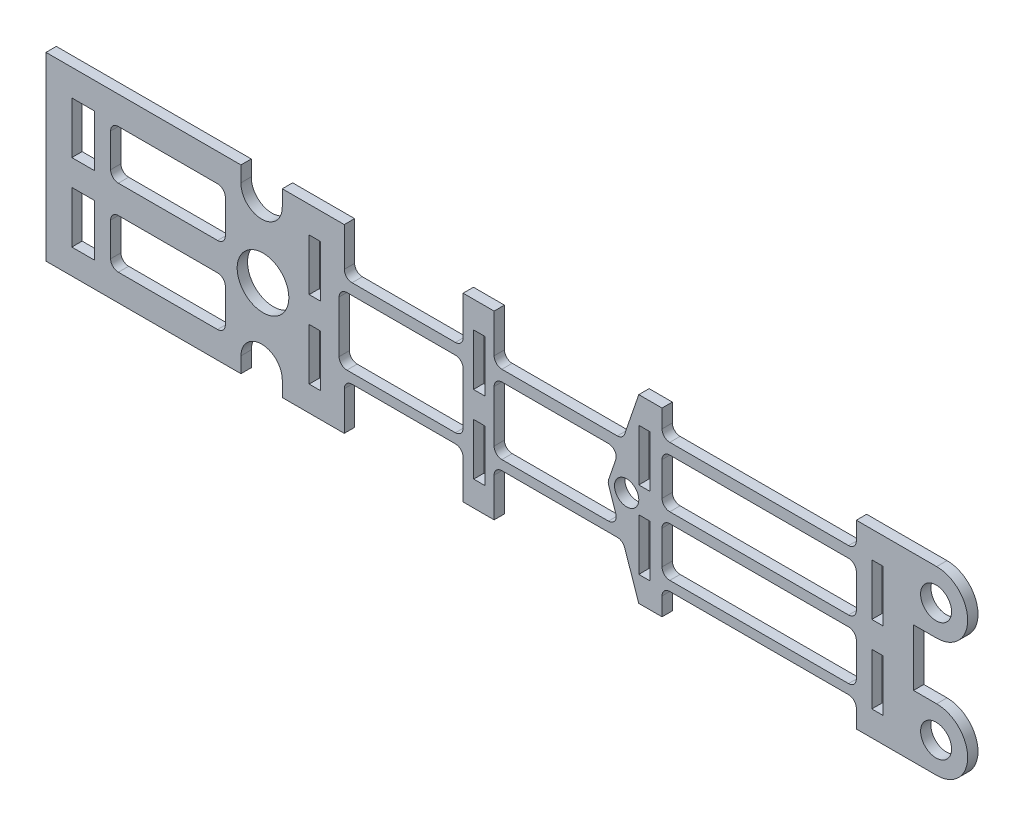
SolidWorks part; units mm, degrees
ref_plane "前视基准面" through (0, 0, 0) normal (0, 0, 1) x (1, 0, 0)
ref_plane "上视基准面" through (0, 0, 0) normal (0, 1, 0) x (1, 0, 0)
ref_plane "右视基准面" through (0, 0, 0) normal (1, 0, 0) x (0, 0, -1)
sketch "Model" plane through (0, 0, 0) normal (0, 0, 1) x (1, 0, 0)
  line L0 (55.9533, 32.4051) -> (58.1533, 32.4051)
  line L1 (58.1533, 32.4051) -> (58.1533, 22.4051)
  line L2 (58.1533, 22.4051) -> (55.9533, 22.4051)
  line L3 (55.9533, 22.4051) -> (55.9533, 32.4051)
  line L4 (55.9533, 7.4051) -> (58.1533, 7.4051)
  line L5 (58.1533, 7.4051) -> (58.1533, 17.4051)
  line L6 (58.1533, 17.4051) -> (55.9533, 17.4051)
  line L7 (55.9533, 17.4051) -> (55.9533, 7.4051)
  line L8 (167.0525, 22.4051) -> (164.8525, 22.4051)
  line L9 (164.8525, 22.4051) -> (164.8525, 32.4051)
  line L10 (164.8525, 32.4051) -> (167.0525, 32.4051)
  line L11 (167.0525, 32.4051) -> (167.0525, 22.4051)
  line L12 (167.0525, 7.4051) -> (167.0525, 17.4051)
  line L13 (167.0525, 17.4051) -> (164.8525, 17.4051)
  line L14 (164.8525, 17.4051) -> (164.8525, 7.4051)
  line L15 (164.8525, 7.4051) -> (167.0525, 7.4051)
  line L16 (119.7532, 32.4051) -> (121.9532, 32.4051)
  line L17 (121.9532, 32.4051) -> (121.9532, 22.4051)
  line L18 (121.9532, 22.4051) -> (119.7532, 22.4051)
  line L19 (119.7532, 22.4051) -> (119.7532, 32.4051)
  line L20 (119.7532, 7.4051) -> (121.9532, 7.4051)
  line L21 (121.9532, 7.4051) -> (121.9532, 17.4051)
  line L22 (121.9532, 17.4051) -> (119.7532, 17.4051)
  line L23 (119.7532, 17.4051) -> (119.7532, 7.4051)
  line L24 (87.7533, 32.4051) -> (89.9533, 32.4051)
  line L25 (89.9533, 32.4051) -> (89.9533, 22.4075)
  line L26 (89.9533, 22.4075) -> (87.7533, 22.4051)
  line L27 (87.7533, 22.4051) -> (87.7533, 32.4051)
  line L28 (87.7999, 7.3998) -> (89.9999, 7.3998)
  line L29 (89.9999, 7.3998) -> (89.9533, 17.3998)
  line L30 (89.9533, 17.3998) -> (87.7999, 17.3998)
  line L31 (87.7999, 17.3998) -> (87.7999, 7.3998)
  line L32 (63.2533, 26.4051) -> (84.2533, 26.4051)
  line L33 (85.7533, 24.9051) -> (85.7533, 14.9051)
  line L34 (84.2533, 13.4051) -> (63.2533, 13.4051)
  line L35 (61.7533, 14.9051) -> (61.7533, 24.9051)
  line L36 (113.8817, 13.4051) -> (93.2533, 13.4051)
  line L37 (91.7533, 14.9051) -> (91.7533, 24.9051)
  line L38 (93.2533, 26.4051) -> (113.8817, 26.4051)
  line L39 (115.3007, 24.4186) -> (113.92, 20.3916)
  line L40 (113.92, 19.4186) -> (115.3007, 15.3916)
  line L41 (42.7544, 5.5422) -> (42.7544, 2.5422)
  line L42 (62.7533, 37.5422) -> (62.7533, 30.0422)
  line L43 (64.2533, 28.5422) -> (84.2533, 28.5422)
  line L44 (85.7533, 30.0422) -> (85.7533, 37.5422)
  line L45 (85.7533, 37.5422) -> (91.7533, 37.5422)
  line L46 (91.7533, 37.5422) -> (91.7533, 30.0422)
  line L47 (93.2533, 28.5422) -> (115.596, 28.5422)
  line L48 (117.015, 29.5557) -> (119.7532, 37.5422)
  line L49 (119.7532, 37.5422) -> (124.2525, 37.5422)
  line L50 (124.2525, 37.5422) -> (124.2525, 34.0422)
  line L51 (125.7525, 32.5422) -> (160.3525, 32.5422)
  line L52 (161.8525, 34.0422) -> (161.8525, 37.5422)
  line L53 (161.8525, 37.5422) -> (177.4044, 37.5422)
  line L54 (177.4044, 25.5422) -> (172.9225, 25.5422)
  line L55 (172.9225, 25.5422) -> (172.9225, 14.5422)
  line L56 (172.9225, 14.5422) -> (177.4044, 14.5422)
  line L57 (177.4044, 2.5422) -> (161.8525, 2.5422)
  line L58 (161.8525, 2.5422) -> (161.8525, 6.0422)
  line L59 (160.3525, 7.5422) -> (125.7525, 7.5422)
  line L60 (124.2525, 6.0422) -> (124.2525, 2.5422)
  line L61 (124.2525, 2.5422) -> (119.7532, 2.5422)
  line L62 (119.7532, 2.5422) -> (117.015, 10.5287)
  line L63 (115.596, 11.5422) -> (93.2533, 11.5422)
  line L64 (91.7533, 10.0422) -> (91.7533, 2.5422)
  line L65 (91.7533, 2.5422) -> (85.7533, 2.5422)
  line L66 (85.7533, 2.5422) -> (85.7533, 10.0422)
  line L67 (84.2533, 11.5422) -> (64.2533, 11.5422)
  line L68 (62.7533, 10.0422) -> (62.7533, 2.5422)
  line L69 (62.7533, 2.5422) -> (50.7523, 2.5422)
  line L70 (50.7523, 2.5422) -> (50.7538, 5.475)
  line L71 (42.7544, 2.5422) -> (5.0248, 2.5422)
  line L72 (42.7544, 34.5422) -> (42.7544, 37.5422)
  line L73 (62.7533, 37.5422) -> (50.7523, 37.5422)
  line L74 (50.7523, 37.5422) -> (50.7523, 34.5422)
  line L75 (42.7544, 37.5422) -> (5.0248, 37.5422)
  line L76 (5.0248, 2.5422) -> (5.0248, 37.5422)
  line L77 (161.8525, 22.4051) -> (161.8525, 28.9051)
  line L78 (160.3525, 30.4051) -> (125.7525, 30.4051)
  line L79 (124.2525, 28.9051) -> (124.2525, 22.4051)
  line L80 (125.7525, 20.9051) -> (160.3525, 20.9051)
  line L81 (124.2525, 17.4051) -> (124.2525, 10.9051)
  line L82 (125.7525, 9.4051) -> (160.3525, 9.4051)
  line L83 (161.8525, 10.9051) -> (161.8525, 17.4051)
  line L84 (160.3525, 18.9051) -> (125.7525, 18.9051)
  line L85 (10.0248, 32.4051) -> (14.4248, 32.4051)
  line L86 (10.0248, 22.4051) -> (14.4248, 22.4051)
  line L87 (10.0248, 17.4051) -> (14.4248, 17.4051)
  line L88 (10.0248, 7.4051) -> (14.4248, 7.4051)
  line L89 (10.0248, 32.4051) -> (10.0248, 22.4051)
  line L90 (14.4248, 32.4051) -> (14.4248, 22.4051)
  line L91 (10.0248, 17.4051) -> (10.0248, 7.4051)
  line L92 (14.4248, 17.4051) -> (14.4248, 7.4051)
  line L93 (19.0245, 17.1915) -> (38.2285, 17.1915)
  line L94 (39.7285, 15.6915) -> (39.7285, 9.1915)
  line L95 (38.2285, 7.6915) -> (19.0245, 7.6915)
  line L96 (17.5245, 9.1915) -> (17.5245, 15.6915)
  line L97 (19.0245, 22.6187) -> (38.2285, 22.6187)
  line L98 (39.7285, 24.1187) -> (39.7285, 30.6187)
  line L99 (38.2285, 32.1187) -> (19.0245, 32.1187)
  line L100 (17.5245, 30.6187) -> (17.5245, 24.1187)
  circle A0 centre (177.2919, 31.4051) radius 3
  circle A1 centre (177.2919, 8.4051) radius 3
  circle A2 centre (117.4032, 19.9051) radius 2.35
  circle A3 centre (47.0264, 19.9051) radius 5
  arc A4 (63.2533, 26.4051) -> (61.7533, 24.9051) centre (63.2533, 24.9051) ccw
  arc A5 (85.7533, 24.9051) -> (84.2533, 26.4051) centre (84.2533, 24.9051) ccw
  arc A6 (84.2533, 13.4051) -> (85.7533, 14.9051) centre (84.2533, 14.9051) ccw
  arc A7 (61.7533, 14.9051) -> (63.2533, 13.4051) centre (63.2533, 14.9051) ccw
  arc A8 (50.7538, 5.475) -> (42.7544, 5.5422) centre (46.7541, 5.5086) ccw
  arc A9 (62.7533, 30.0422) -> (64.2533, 28.5422) centre (64.2533, 30.0422) ccw
  arc A10 (84.2533, 28.5422) -> (85.7533, 30.0422) centre (84.2533, 30.0422) ccw
  arc A11 (91.7533, 30.0422) -> (93.2533, 28.5422) centre (93.2533, 30.0422) ccw
  arc A12 (115.596, 28.5422) -> (117.015, 29.5557) centre (115.596, 30.0422) ccw
  arc A13 (124.2525, 34.0422) -> (125.7525, 32.5422) centre (125.7525, 34.0422) ccw
  arc A14 (160.3525, 32.5422) -> (161.8525, 34.0422) centre (160.3525, 34.0422) ccw
  arc A15 (177.4044, 25.5422) -> (177.4044, 37.5422) centre (177.4044, 31.5422) ccw
  arc A16 (177.4044, 2.5422) -> (177.4044, 14.5422) centre (177.4044, 8.5422) ccw
  arc A17 (161.8525, 6.0422) -> (160.3525, 7.5422) centre (160.3525, 6.0422) ccw
  arc A18 (125.7525, 7.5422) -> (124.2525, 6.0422) centre (125.7525, 6.0422) ccw
  arc A19 (117.015, 10.5287) -> (115.596, 11.5422) centre (115.596, 10.0422) ccw
  arc A20 (93.2533, 11.5422) -> (91.7533, 10.0422) centre (93.2533, 10.0422) ccw
  arc A21 (85.7533, 10.0422) -> (84.2533, 11.5422) centre (84.2533, 10.0422) ccw
  arc A22 (64.2533, 11.5422) -> (62.7533, 10.0422) centre (64.2533, 10.0422) ccw
  arc A23 (42.7544, 34.5422) -> (50.7523, 34.5422) centre (46.7533, 34.4579) ccw
  arc A24 (19.0245, 17.1915) -> (17.5245, 15.6915) centre (19.0245, 15.6915) ccw
  arc A25 (39.7285, 15.6915) -> (38.2285, 17.1915) centre (38.2285, 15.6915) ccw
  arc A26 (38.2285, 7.6915) -> (39.7285, 9.1915) centre (38.2285, 9.1915) ccw
  arc A27 (17.5245, 9.1915) -> (19.0245, 7.6915) centre (19.0245, 9.1915) ccw
  arc A28 (17.5245, 24.1187) -> (19.0245, 22.6187) centre (19.0245, 24.1187) ccw
  arc A29 (38.2285, 22.6187) -> (39.7285, 24.1187) centre (38.2285, 24.1187) ccw
  arc A30 (39.7285, 30.6187) -> (38.2285, 32.1187) centre (38.2285, 30.6187) ccw
  arc A31 (19.0245, 32.1187) -> (17.5245, 30.6187) centre (19.0245, 30.6187) ccw
  arc A32 (113.8817, 13.4051) -> (115.3007, 15.3916) centre (113.8817, 14.9051) ccw
  arc A33 (91.7533, 14.9051) -> (93.2533, 13.4051) centre (93.2533, 14.9051) ccw
  arc A34 (93.2533, 26.4051) -> (91.7533, 24.9051) centre (93.2533, 24.9051) ccw
  arc A35 (115.3007, 24.4186) -> (113.8817, 26.4051) centre (113.8817, 24.9051) ccw
  arc A36 (113.92, 20.3916) -> (113.92, 19.4186) centre (115.3389, 19.9051) ccw
  arc A37 (161.8525, 28.9051) -> (160.3525, 30.4051) centre (160.3525, 28.9051) ccw
  arc A38 (125.7525, 30.4051) -> (124.2525, 28.9051) centre (125.7525, 28.9051) ccw
  arc A39 (124.2525, 22.4051) -> (125.7525, 20.9051) centre (125.7525, 22.4051) ccw
  arc A40 (160.3525, 20.9051) -> (161.8525, 22.4051) centre (160.3525, 22.4051) ccw
  arc A41 (124.2525, 10.9051) -> (125.7525, 9.4051) centre (125.7525, 10.9051) ccw
  arc A42 (160.3525, 9.4051) -> (161.8525, 10.9051) centre (160.3525, 10.9051) ccw
  arc A43 (161.8525, 17.4051) -> (160.3525, 18.9051) centre (160.3525, 17.4051) ccw
  arc A44 (125.7525, 18.9051) -> (124.2525, 17.4051) centre (125.7525, 17.4051) ccw
  point P179 (0, 0)
  point P193 (0, 0)
  point P194 (50.8883, 3.414)
extrude "凸台-拉伸1" add sketch "Model" along normal blind 2
